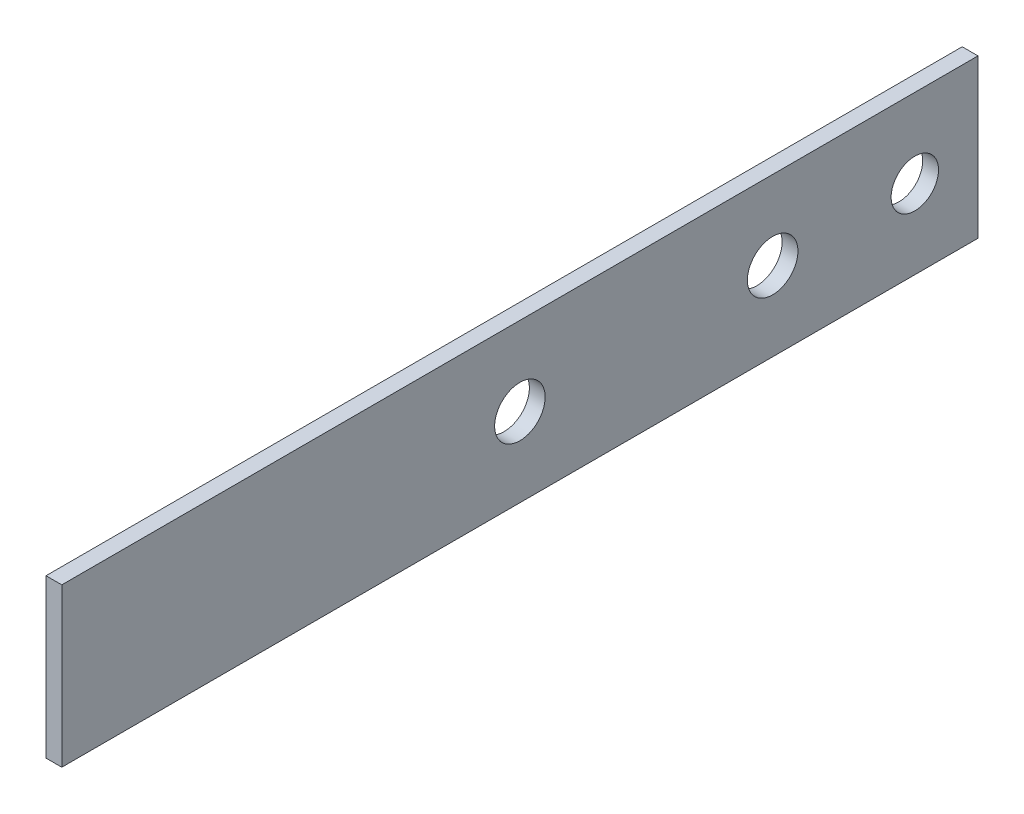
SolidWorks part; units mm, degrees
material "镀铬不锈钢"
ref_plane "前视基准面" through (0, 0, 0) normal (0, 0, 1) x (1, 0, 0)
ref_plane "上视基准面" through (0, 0, 0) normal (0, 1, 0) x (1, 0, 0)
ref_plane "右视基准面" through (0, 0, 0) normal (1, 0, 0) x (0, 0, -1)
sketch "草图1" plane through (0, 0, 0) normal (1, 0, 0) x (0, 0, -1)
  line L1 (-29, -5) -> (29, -5)
  line L2 (-29, -5) -> (-29, 5)
  line L3 (-29, 5) -> (29, 5)
  line L4 (29, -5) -> (29, 5)
  line L5 (-29, -5) -> (29, 5) construction
  line L6 (-29, 5) -> (29, -5) construction
  point P0 (0, 0)
  dimension "D1" = 10
  dimension "D2" = 58
extrude "凸台-拉伸1" add sketch "草图1" along normal blind 1
hole_wizard "M3 间隙孔1" positions "草图3" profile "草图2" hole size "M3" standard "GB" end condition up to next
sketch "草图3" plane through (1, 0, 0) normal (1, 0, 0) x (0, 0, -1)
  line L1 (29, -5) -> (29, 5) construction
  point P0 (16, 0)
  point P10 (0, 0)
  dimension "D1" = 13
  dimension "D2" = 16
sketch "草图2" plane through (1, 0, -16) normal (0, 1, 0) x (0, 0, -1)
  line L0 (0, 0) -> (0, 1)
  line L1 (0, 1) -> (1.6, 1)
  line L2 (1.6, 1) -> (1.6, 0)
  line L5 (1.6, 0) -> (0, 0)
  line L11 (0, -6.35) -> (0, 107.95) construction
  dimension "通孔孔直径" = 3.2
  dimension "通孔孔深度" = 1
hole_wizard "M3 螺纹孔1" positions "草图5" profile "草图4" tap size "M3" standard "GB" end condition up to next
sketch "草图5" plane through (1, 0, 0) normal (1, 0, 0) x (0, 0, -1)
  line L0 (29, -5) -> (29, 5) construction
  point P0 (25, 0)
  dimension "D1" = 4
sketch "草图4" plane through (1, 0, -25) normal (0, 1, 0) x (0, 0, -1)
  line L0 (0, 0) -> (0, 1)
  line L1 (0, 1) -> (1.5, 1)
  line L2 (1.5, 1) -> (1.5, 0)
  line L5 (1.5, 0) -> (0, 0)
  line L11 (0, -6.35) -> (0, 107.95) construction
  dimension "螺纹线主直径" = 3
  dimension "通孔螺纹孔钻头深度" = 1
